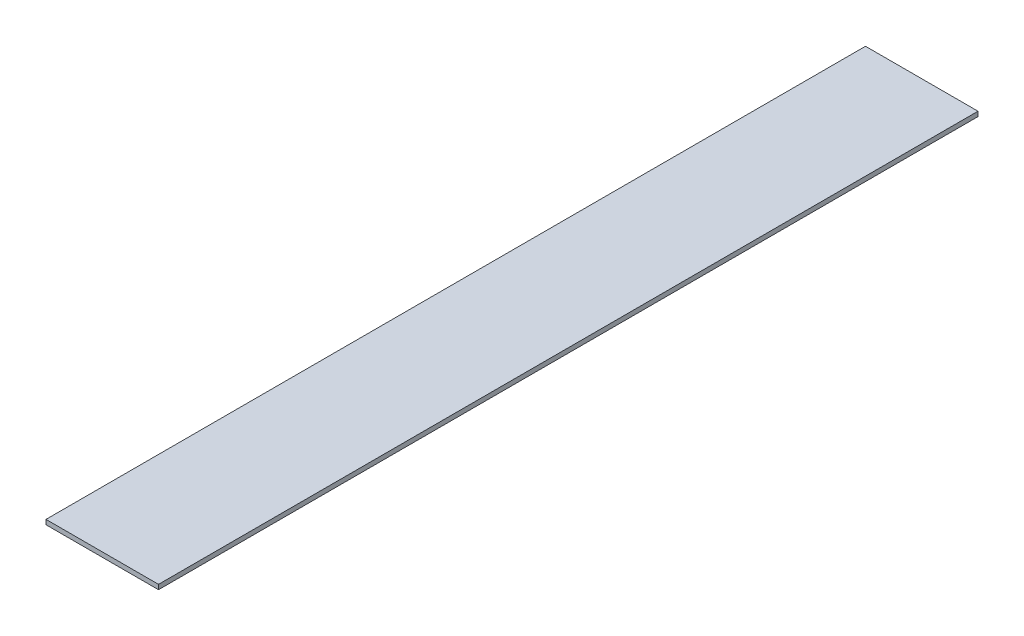
SolidWorks part; units mm, degrees
ref_plane "Front Plane" through (0, 0, 0) normal (0, 0, 1) x (1, 0, 0)
ref_plane "Top Plane" through (0, 0, 0) normal (0, 1, 0) x (1, 0, 0)
ref_plane "Right Plane" through (0, 0, 0) normal (1, 0, 0) x (0, 0, -1)
sketch "Sketch1" plane through (0, 0, 0) normal (0, 1, 0) x (1, 0, 0)
  line L1 (465, 277.5) -> (-465, 277.5)
  line L2 (465, 277.5) -> (465, -277.5)
  line L3 (465, -277.5) -> (-465, -277.5)
  line L4 (-465, 277.5) -> (-465, -277.5)
  line L5 (465, 277.5) -> (-465, -277.5) construction
  line L6 (465, -277.5) -> (-465, 277.5) construction
  line L7 (388.8, 239.4) -> (-388.8, 239.4)
  line L8 (388.8, 239.4) -> (388.8, -239.4)
  line L9 (388.8, -239.4) -> (-388.8, -239.4)
  line L10 (-388.8, 239.4) -> (-388.8, -239.4)
  line L11 (388.8, 239.4) -> (-388.8, -239.4) construction
  line L12 (388.8, -239.4) -> (-388.8, 239.4) construction
  point P0 (0, 0)
  point P6 (0, 0)
  dimension "D1" = 76.2
  dimension "D2" = 555
  dimension "D3" = 38.1
  dimension "D4" = 930
extrude "Boss-Extrude2" add sketch "Sketch1" along normal blind 3.175
sketch "Sketch2" plane through (0, 3.175, 0) normal (0, 1, 0) x (1, 0, 0)
  line L0 (465, 277.5) -> (-465, 277.5) construction
  line L1 (-388.8, 277.5) -> (465, 277.5)
  line L2 (-388.8, 277.5) -> (-388.8, -277.5)
  line L3 (-388.8, -277.5) -> (465, -277.5)
  line L4 (465, 277.5) -> (465, -277.5)
  line L5 (-388.8, 239.4) -> (-388.8, -239.4) construction
extrude "Cut-Extrude1" cut sketch "Sketch2" against normal through all both and the other way through all
